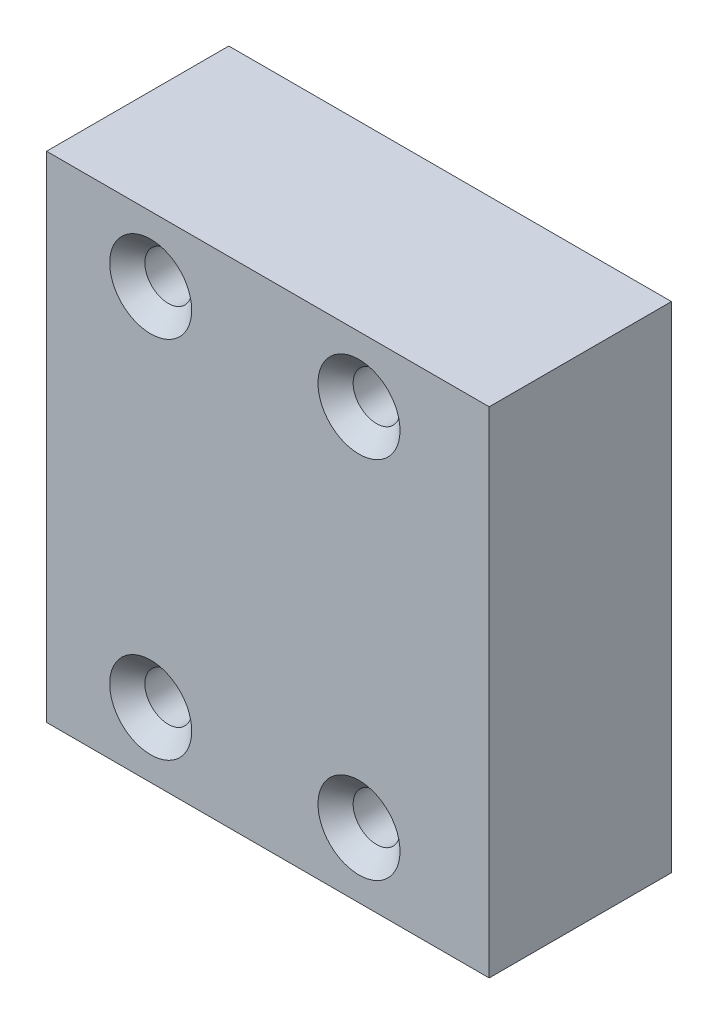
SolidWorks part; units mm, degrees
ref_plane "Front Plane" through (0, 0, 0) normal (0, 0, 1) x (1, 0, 0)
ref_plane "Top Plane" through (0, 0, 0) normal (0, 1, 0) x (1, 0, 0)
ref_plane "Right Plane" through (0, 0, 0) normal (1, 0, 0) x (0, 0, -1)
sketch "Sketch1" plane through (0, 0, 0) normal (0, 0, 1) x (1, 0, 0)
  line L1 (17, -19) -> (-17, -19)
  line L2 (17, -19) -> (17, 19)
  line L3 (17, 19) -> (-17, 19)
  line L4 (-17, -19) -> (-17, 19)
  line L5 (17, -19) -> (-17, 19) construction
  line L6 (17, 19) -> (-17, -19) construction
  point P0 (0, 0)
  dimension "D1" = 34
  dimension "D2" = 38
extrude "Boss-Extrude1" add sketch "Sketch1" along normal blind 14
hole_wizard "CSK for M3 Flat Head Machine Screw1" positions "Sketch2" profile "Sketch3" countersink size "M3" standard "ANSI Metric" end condition through all
sketch "Sketch2" plane through (0, 0, 14) normal (0, 0, 1) x (1, 0, 0)
  line L0 (-17, -19) -> (17, -19) construction
  line L1 (17, -19) -> (17, 19) construction
  line L2 (17, 19) -> (-17, 19) construction
  point P0 (-9, 14)
  point P2 (-9, -14)
  point P4 (7, -14)
  point P6 (7, 14)
  point P9 (0, 0)
  point P10 (0, 0)
  point P11 (0, 0)
  point P12 (0, 0)
  dimension "D1" = 5
  dimension "D2" = 10
  dimension "D3" = 16
  dimension "D4" = 28
  dimension "D5" = 5
sketch "Sketch3" plane through (-9, 14, 14) normal (1, 0, 0) x (0, -1, 0)
  line L0 (0, 0) -> (0, 14)
  line L1 (0, 14) -> (1.8, 14)
  line L2 (1.8, 14) -> (1.8, 1.35)
  line L3 (1.8, 1.35) -> (3.15, 0)
  line L5 (3.15, 0) -> (0, 0)
  line L6 (-1.8, 1.35) -> (-3.15, 0) construction
  line L11 (0, -6.35) -> (0, 107.95) construction
  dimension "Thru Hole Dia." = 3.6
  dimension "Thru Hole Depth" = 14
  dimension "Near C'Sink Dia." = 6.3
  dimension "Near C'Sink Angle" = 90
